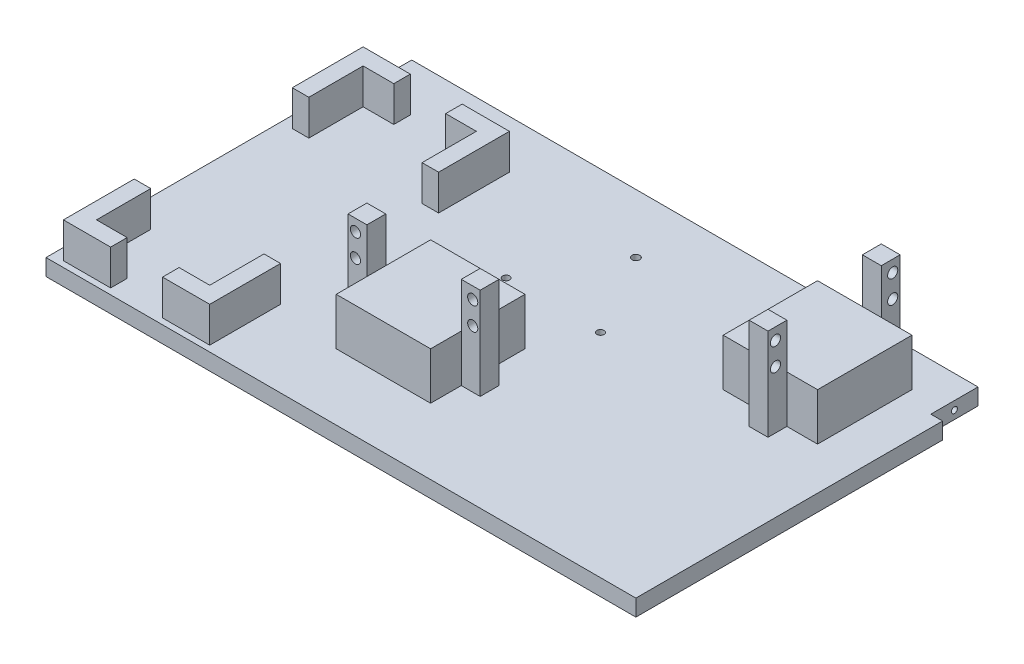
SolidWorks part; units mm, degrees
ref_plane "Ebene vorne" through (0, 0, 0) normal (0, 0, 1) x (1, 0, 0)
ref_plane "Ebene oben" through (0, 0, 0) normal (0, 1, 0) x (1, 0, 0)
ref_plane "Ebene rechts" through (0, 0, 0) normal (1, 0, 0) x (0, 0, -1)
sketch "Skizze1" plane through (0, 0, 0) normal (0, 1, 0) x (1, 0, 0)
  line L1 (-125, -125) -> (125, -125)
  line L2 (-125, -125) -> (-125, 125)
  line L3 (-125, 125) -> (125, 125)
  line L4 (125, -125) -> (125, 125)
  line L5 (-125, -125) -> (125, 125) construction
  line L6 (-125, 125) -> (125, -125) construction
  point P0 (0, 0)
  dimension "D1" = 250
  dimension "D2" = 250
extrude "Aufsatz-Linear austragen1" add sketch "Skizze1" along normal blind 5
sketch "Skizze2" plane through (0, 5, 0) normal (0, 1, 0) x (1, 0, 0)
  line L1 (-112.1275, -114.481) -> (-66.1275, -114.481)
  line L2 (-112.1275, -114.481) -> (-112.1275, -3.481)
  line L3 (-112.1275, -3.481) -> (-66.1275, -3.481)
  line L4 (-66.1275, -114.481) -> (-66.1275, -3.481)
  line L5 (-108.0153, 50.9925) -> (-23.0153, 50.9925)
  line L6 (-108.0153, 50.9925) -> (-108.0153, 110.9925)
  line L7 (-108.0153, 110.9925) -> (-23.0153, 110.9925)
  line L8 (-23.0153, 50.9925) -> (-23.0153, 110.9925)
  line L9 (-20, -105) -> (20, -105)
  line L10 (-20, -105) -> (-20, -65)
  line L11 (-20, -65) -> (20, -65)
  line L12 (20, -105) -> (20, -65)
  line L13 (65, -20) -> (105, -20)
  line L14 (65, -20) -> (65, 20)
  line L15 (65, 20) -> (105, 20)
  line L16 (105, -20) -> (105, 20)
  line L17 (6.7738, 50.9925) -> (91.7738, 50.9925)
  line L18 (6.7738, 50.9925) -> (6.7738, 110.9925)
  line L19 (6.7738, 110.9925) -> (91.7738, 110.9925)
  line L20 (91.7738, 50.9925) -> (91.7738, 110.9925)
  line L21 (-125, 125) -> (-125, -125) construction
  line L22 (-125, -125) -> (125, -125) construction
  line L23 (-100.1275, -122.481) -> (-100.1275, 4.519)
  line L24 (-120.1275, -122.481) -> (-58.1275, -122.481)
  line L25 (-120.1275, -122.481) -> (-120.1275, 4.519)
  line L26 (-120.1275, 4.519) -> (-58.1275, 4.519)
  line L27 (-58.1275, -122.481) -> (-58.1275, 4.519)
  line L28 (-78.1275, -122.481) -> (-78.1275, 4.519)
  line L29 (-120.1275, -92.481) -> (-57.4038, -92.481)
  line L30 (-120.1275, -25.481) -> (-58.1275, -25.481)
  circle A0 centre (0, 0) radius 1.65
  dimension "D1" = 3.3
  dimension "D2" = 46
  dimension "D3" = 111
  dimension "D4" = 40
  dimension "D5" = 40
  dimension "D6" = 60
  dimension "D7" = 85
  dimension "D8" = 40
  dimension "D9" = 40
  dimension "D10" = 65
  dimension "D11" = 125
  dimension "D12" = 125
  dimension "D13" = 65
  dimension "D14" = 105
  dimension "D15" = 105
  dimension "D16" = 8
  dimension "D17" = 8
  dimension "D18" = 8
  dimension "D19" = 8
  dimension "D20" = 30
  dimension "D21" = 30
  dimension "D22" = 20
  dimension "D23" = 20
extrude "Aufsatz-Linear austragen2" add sketch "Skizze2" along normal blind 15 contours L29 L25 L24 L23 L1 L2 | L29 L4 L1 L28 L24 L27 | L4 L30 L27 L26 L28 L3 | L25 L30 L2 L3 L23 L26 | L9 L12 L11 L10 | L13 L16 L15 L14
sketch "Skizze3" plane through (0, 20, 0) normal (0, 1, 0) x (1, 0, 0)
  line L0 (65, -20) -> (65, 20) construction
  line L1 (-20, -105) -> (20, -105)
  line L2 (-20, -105) -> (-20, -65)
  line L3 (-20, -65) -> (20, -65)
  line L4 (20, -105) -> (20, -65)
  line L5 (65, -20) -> (105, -20)
  line L6 (65, -20) -> (65, 20)
  line L7 (65, 20) -> (105, 20)
  line L8 (105, -20) -> (105, 20)
  line L9 (70, -15) -> (100, -15)
  line L10 (70, -15) -> (70, 15)
  line L11 (70, 15) -> (100, 15)
  line L12 (100, -15) -> (100, 15)
  line L13 (-15, -100) -> (15, -100)
  line L14 (-15, -100) -> (-15, -70)
  line L15 (-15, -70) -> (15, -70)
  line L16 (15, -100) -> (15, -70)
  circle A0 centre (0, 0) radius 1.65
  dimension "D9" = 3.3
  dimension "D1" = 5
  dimension "D2" = 5
  dimension "D3" = 5
  dimension "D4" = 5
  dimension "D5" = 5
  dimension "D6" = 5
  dimension "D7" = 5
  dimension "D8" = 5
extrude "Schnitt-Linear austragen1" cut sketch "Skizze3" against normal blind 15 contours L14 L13 L16 L15 | L10 L9 L12 L11 | A0
sketch "Skizze4" plane through (0, 5, 0) normal (0, 1, 0) x (1, 0, 0)
  line L1 (-15, -100) -> (15, -100)
  line L2 (-15, -100) -> (-15, -70)
  line L3 (-15, -70) -> (15, -70)
  line L4 (15, -100) -> (15, -70)
  line L5 (70, -15) -> (100, -15)
  line L6 (70, -15) -> (70, 15)
  line L7 (70, 15) -> (100, 15)
  line L8 (100, -15) -> (100, 15)
  circle A0 centre (0, 0) radius 1.65
  dimension "D1" = 3.3
extrude "Schnitt-Linear austragen2" cut sketch "Skizze4" against normal blind 15
sketch "Skizze6" plane through (0, 20, 0) normal (0, 1, 0) x (1, 0, 0)
  line L1 (-20, -105) -> (20, -105)
  line L2 (-20, -105) -> (-20, -65)
  line L3 (-20, -65) -> (20, -65)
  line L4 (20, -105) -> (20, -65)
  line L5 (65, -20) -> (105, -20)
  line L6 (65, -20) -> (65, 20)
  line L7 (65, 20) -> (105, 20)
  line L8 (105, -20) -> (105, 20)
extrude "Aufsatz-Linear austragen3" add sketch "Skizze6" against normal blind 5
sketch "Skizze7" plane through (0, 5, 0) normal (0, 1, 0) x (1, 0, 0)
  line L12 (-20, -105) -> (20, -105)
  line L13 (-20, -105) -> (-20, -65)
  line L14 (-20, -65) -> (20, -65)
  line L15 (20, -105) -> (20, -65)
  line L16 (65, -20) -> (105, -20)
  line L17 (65, -20) -> (65, 20)
  line L18 (65, 20) -> (105, 20)
  line L19 (105, -20) -> (105, 20)
extrude "Schnitt-Linear austragen3" cut sketch "Skizze7" along normal blind 43
sketch "Skizze8" plane through (0, 5, 0) normal (0, 1, 0) x (1, 0, 0)
  line L1 (-15, -100) -> (15, -100)
  line L2 (-15, -100) -> (-15, -70)
  line L3 (-15, -70) -> (15, -70)
  line L4 (15, -100) -> (15, -70)
  line L5 (70, -15) -> (100, -15)
  line L6 (70, -15) -> (70, 15)
  line L7 (70, 15) -> (100, 15)
  line L8 (100, -15) -> (100, 15)
extrude "Aufsatz-Linear austragen4" add sketch "Skizze8" against normal blind 5
sketch "Skizze9" plane through (0, 5, 0) normal (0, 1, 0) x (1, 0, 0)
  line L0 (0, -71) -> (0, -34.8212)
  line L1 (-6, -116) -> (39, -116)
  line L2 (-6, -116) -> (-6, -71)
  line L3 (-6, -71) -> (39, -71)
  line L4 (39, -116) -> (39, -71)
  line L5 (71, -39) -> (116, -39)
  line L6 (71, -39) -> (71, 6)
  line L7 (71, 6) -> (116, 6)
  line L8 (116, -39) -> (116, 6)
  line L9 (71, 0) -> (36.9303, 0)
  line L10 (125, 125) -> (-125, 125) construction
  line L11 (125, -125) -> (125, 125) construction
  dimension "D1" = 45
  dimension "D2" = 45
  dimension "D3" = 45
  dimension "D4" = 45
  dimension "D5" = 71
  dimension "D6" = 71
  dimension "D7" = 6
  dimension "D8" = 6
  dimension "D9" = 125
  dimension "D10" = 125
extrude "Aufsatz-Linear austragen5" add sketch "Skizze9" along normal blind 15 contours L1 L4 L3 L2 | L5 L8 L7 L6
sketch "Skizze10" plane through (0, 5, 0) normal (0, 1, 0) x (1, 0, 0)
  line L0 (-6, -116) -> (-6, -71) construction
  line L1 (-6, -93) -> (-14, -93)
  line L2 (-6, -93) -> (-6, -85)
  line L3 (-6, -85) -> (-14, -85)
  line L4 (-14, -93) -> (-14, -85)
  line L5 (39, -116) -> (39, -71) construction
  line L6 (39, -93) -> (47, -93)
  line L7 (39, -93) -> (39, -85)
  line L8 (39, -85) -> (47, -85)
  line L9 (47, -93) -> (47, -85)
  line L15 (71, 6) -> (116, 6) construction
  line L16 (93, 6) -> (85, 6)
  line L17 (93, 6) -> (93, 14)
  line L18 (93, 14) -> (85, 14)
  line L19 (85, 6) -> (85, 14)
  line L22 (71, -39) -> (71, 6) construction
  line L23 (85, -39) -> (93, -39)
  line L24 (85, -39) -> (85, -47)
  line L25 (85, -47) -> (93, -47)
  line L26 (93, -39) -> (93, -47)
  line L27 (-6, -71) -> (39, -71) construction
  line L28 (-6, -71) -> (39, -71) construction
  dimension "D1" = 8
  dimension "D2" = 8
  dimension "D3" = 14
  dimension "D4" = 8
  dimension "D5" = 8
  dimension "D7" = 8
  dimension "D8" = 14
  dimension "D9" = 8
  dimension "D10" = 14
  dimension "D11" = 14
  dimension "D12" = 8
  dimension "D13" = 8
extrude "Aufsatz-Linear austragen6" add sketch "Skizze10" along normal blind 34 contours L7 L6 L9 L8 | L2 L1 L4 L3 | L24 L23 L26 L25 | L17 L16 L19 L18
sketch "Skizze11" plane through (0, 0, 85) normal (0, 0, -1) x (-1, 0, 0)
  line L0 (-47, 39) -> (-47, 5) construction
  line L1 (14, 39) -> (6, 39)
  line L2 (14, 39) -> (14, 20)
  line L3 (14, 20) -> (6, 20)
  line L4 (6, 39) -> (6, 20)
  line L5 (-39, 39) -> (-47, 39)
  line L6 (-39, 39) -> (-39, 20)
  line L7 (-39, 20) -> (-47, 20)
  line L8 (-47, 39) -> (-47, 20)
  line L9 (10.85, 31.9) -> (10.85, 26.5)
  line L10 (-43.85, 31.9) -> (-43.85, 26.5)
  circle A0 centre (10.85, 34.05) radius 2.15
  circle A1 centre (10.85, 24.35) radius 2.15
  circle A2 centre (-43.85, 34.05) radius 2.15
  circle A3 centre (-43.85, 24.35) radius 2.15
  dimension "D1" = 4.3
  dimension "D2" = 4.3
  dimension "D3" = 4.3
  dimension "D4" = 4.3
  dimension "D5" = 5.4
  dimension "D6" = 3.15
  dimension "D7" = 5.4
  dimension "D8" = 3.15
  dimension "D9" = 4.35
  dimension "D10" = 4.35
extrude "Schnitt-Linear austragen4" cut sketch "Skizze11" against normal blind 34 contours A0 | A1 | A2 | A3
sketch "Skizze12" plane through (0, 5, 0) normal (0, 1, 0) x (1, 0, 0)
  line L0 (71, 0) -> (57, 0)
  line L1 (71, -39) -> (71, 6) construction
  line L2 (125, 125) -> (-125, 125) construction
  line L3 (125, -125) -> (125, 125) construction
  line L4 (0, 0) -> (0, -71)
  line L6 (-6, -71) -> (39, -71) construction
  line L10 (-22.6064, -118.7348) -> (120.4564, -118.7348)
  line L11 (-22.6064, -118.7348) -> (-22.6064, 65.7516)
  line L12 (-22.6064, 65.7516) -> (120.4564, 65.7516)
  line L13 (120.4564, -118.7348) -> (120.4564, 65.7516)
  dimension "D1" = 14
  dimension "D2" = 125
  dimension "D3" = 68
  dimension "D4" = 57
  dimension "D5" = 71
extrude "Schnitt-Linear austragen5" cut sketch "Skizze12" along normal blind 60
sketch "Skizze13" plane through (0, 5, 0) normal (0, 1, 0) x (1, 0, 0)
  line L0 (107, 0) -> (130, 0)
  line L1 (-30, -97) -> (10, -97)
  line L2 (-30, -97) -> (-30, -57)
  line L3 (-30, -57) -> (10, -57)
  line L4 (10, -97) -> (10, -57)
  line L5 (67, -30) -> (107, -30)
  line L6 (67, -30) -> (67, 10)
  line L7 (67, 10) -> (107, 10)
  line L8 (107, -30) -> (107, 10)
  line L9 (-125, -125) -> (125, -125) construction
  line L12 (0, -97) -> (0, -120)
  line L15 (125, -125) -> (125, 125) construction
  dimension "D2" = 120
  dimension "D3" = 125
  dimension "D4" = 130
  dimension "D5" = 23
  dimension "D6" = 10
  dimension "D7" = 125
  dimension "D8" = 40
  dimension "D9" = 40
  dimension "D10" = 23
  dimension "D11" = 40
  dimension "D12" = 40
  dimension "D13" = 10
extrude "Aufsatz-Linear austragen7" add sketch "Skizze13" along normal blind 15 contours L1 L4 L3 L2 | L5 L8 L7 L6
sketch "Skizze14" plane through (0, 5, 0) normal (0, 1, 0) x (1, 0, 0)
  line L0 (-30, -97) -> (-30, -57) construction
  line L1 (-30, -84) -> (-38, -84)
  line L2 (-30, -84) -> (-30, -76)
  line L3 (-30, -76) -> (-38, -76)
  line L4 (-38, -84) -> (-38, -76)
  line L5 (10, -97) -> (10, -57) construction
  line L6 (10, -84) -> (18, -84)
  line L7 (10, -84) -> (10, -76)
  line L8 (10, -76) -> (18, -76)
  line L9 (18, -84) -> (18, -76)
  line L10 (67, -30) -> (107, -30) construction
  line L11 (86, -30) -> (94, -30)
  line L12 (86, -30) -> (86, -38)
  line L13 (86, -38) -> (94, -38)
  line L14 (94, -30) -> (94, -38)
  line L15 (67, 10) -> (107, 10) construction
  line L16 (94, 10) -> (86, 10)
  line L17 (94, 10) -> (94, 18)
  line L18 (94, 18) -> (86, 18)
  line L19 (86, 10) -> (86, 18)
  line L24 (107, -30) -> (107, 10) construction
  line L25 (107, -30) -> (107, 10) construction
  line L26 (-30, -97) -> (10, -97) construction
  dimension "D1" = 8
  dimension "D2" = 8
  dimension "D3" = 8
  dimension "D4" = 8
  dimension "D5" = 8
  dimension "D6" = 8
  dimension "D7" = 8
  dimension "D8" = 8
  dimension "D9" = 13
  dimension "D10" = 13
  dimension "D11" = 13
  dimension "D12" = 13
extrude "Aufsatz-Linear austragen8" add sketch "Skizze14" along normal blind 34
sketch "Skizze15" plane through (0, 5, 0) normal (0, 1, 0) x (1, 0, 0)
  line L0 (125, 125) -> (-125, 125) construction
  line L1 (-18.5, 111) -> (18.5, 111)
  line L2 (-18.5, 111) -> (-18.5, 125)
  line L3 (-18.5, 125) -> (18.5, 125)
  line L4 (18.5, 111) -> (18.5, 125)
  line L5 (-125, 125) -> (-125, -125) construction
  dimension "D1" = 14
  dimension "D2" = 37
  dimension "D3" = 106.5
extrude "Schnitt-Linear austragen6" cut sketch "Skizze15" against normal blind 10 contours L2 L1 L4 L3
sketch "Skizze16" plane through (0, 5, 0) normal (0, 1, 0) x (1, 0, 0)
  line L1 (-101.7331, 41.9857) -> (-51.7331, 41.9857)
  line L2 (-101.7331, 41.9857) -> (-101.7331, 111.9857)
  line L3 (-101.7331, 111.9857) -> (-51.7331, 111.9857)
  line L4 (-51.7331, 41.9857) -> (-51.7331, 111.9857)
  line L5 (27.6532, 40.8623) -> (112.6532, 40.8623)
  line L6 (27.6532, 40.8623) -> (27.6532, 96.6623)
  line L7 (27.6532, 96.6623) -> (112.6532, 96.6623)
  line L8 (112.6532, 40.8623) -> (112.6532, 96.6623)
  dimension "D1" = 70
  dimension "D2" = 50
  dimension "D3" = 85
  dimension "D4" = 55.8
extrude "Aufsatz-Linear austragen9" add sketch "Skizze16" along normal blind 1 contours L2 L1 L4 L3
sketch "Skizze17" plane through (0, 5, 0) normal (0, 1, 0) x (1, 0, 0)
  line L1 (24.3018, 42.8865) -> (109.3018, 42.8865)
  line L2 (24.3018, 42.8865) -> (24.3018, 98.6865)
  line L3 (24.3018, 98.6865) -> (109.3018, 98.6865)
  line L4 (109.3018, 42.8865) -> (109.3018, 98.6865)
  circle A0 centre (105.9518, 46.2865) radius 1.35
  circle A1 centre (105.9518, 95.2865) radius 1.35
  circle A2 centre (47.9518, 46.2865) radius 1.35
  circle A3 centre (47.9518, 95.2865) radius 1.35
  dimension "D3" = 2.7
  dimension "D4" = 2.7
  dimension "D5" = 2.7
  dimension "D6" = 2.7
  dimension "D1" = 85
  dimension "D2" = 55.8
  dimension "D7" = 49
  dimension "D8" = 3.4
  dimension "D9" = 49
  dimension "D10" = 3.4
  dimension "D11" = 58
  dimension "D12" = 58
  dimension "D13" = 3.35
  dimension "D14" = 3.35
extrude "Schnitt-Linear austragen7" cut sketch "Skizze17" against normal blind 21 contours A2 | A3 | A1 | A0
sketch "Skizze18" plane through (0, 0, 76) normal (0, 0, -1) x (-1, 0, 0)
  line L0 (34.85, 36.9) -> (34.85, 31.5)
  line L5 (-14.85, 36.9) -> (-14.85, 31.5)
  line L11 (-10, 43.425) -> (-18, 43.425)
  line L12 (-10, 43.425) -> (-10, 25)
  line L13 (-10, 25) -> (-18, 25)
  line L14 (-18, 43.425) -> (-18, 25)
  line L15 (-18, 39) -> (-18, 5) construction
  line L16 (-18, 5) -> (-10, 5) construction
  line L17 (38, 44) -> (30, 44)
  line L18 (38, 44) -> (38, 25)
  line L19 (38, 25) -> (30, 25)
  line L20 (30, 44) -> (30, 25)
  line L21 (38, 39) -> (38, 5) construction
  line L22 (30, 5) -> (38, 5) construction
  circle A4 centre (-14.85, 39.05) radius 2.15
  circle A5 centre (-14.85, 29.35) radius 2.15
  circle A6 centre (34.85, 39.05) radius 2.15
  circle A7 centre (34.85, 29.35) radius 2.15
  dimension "D2" = 4.3
  dimension "D6" = 4.3
  dimension "D7" = 4.3
  dimension "D3" = 4.3
  dimension "D4" = 5.4
  dimension "D5" = 4.35
  dimension "D8" = 4.35
  dimension "D9" = 5.4
  dimension "D10" = 3.15
  dimension "D11" = 0
  dimension "D12" = 20
  dimension "D13" = 3.15
  dimension "D14" = 0
  dimension "D15" = 20
extrude "Schnitt-Linear austragen8" cut sketch "Skizze18" against normal blind 21 contours A6 | A7 | A4 | A5
sketch "Skizze19" plane through (86, 0, 0) normal (-1, 0, 0) x (0, 0, 1)
  line L0 (34.8363, 36.9) -> (34.8363, 31.5)
  line L5 (-14.85, 36.9) -> (-14.85, 31.5)
  line L11 (37.9863, 44) -> (30, 44)
  line L12 (37.9863, 44) -> (37.9863, 25)
  line L13 (37.9863, 25) -> (30, 25)
  line L14 (30, 44) -> (30, 25)
  line L15 (30, 5) -> (38, 5) construction
  line L16 (30, 39) -> (30, 20) construction
  line L18 (-10, 43.7954) -> (-18, 43.7954)
  line L19 (-10, 43.7954) -> (-10, 25)
  line L20 (-10, 25) -> (-18, 25)
  line L21 (-18, 43.7954) -> (-18, 25)
  line L22 (-18, 39) -> (-18, 5) construction
  line L23 (-125, 5) -> (125, 5) construction
  circle A4 centre (34.8363, 39.05) radius 2.15
  circle A5 centre (34.8363, 29.35) radius 2.15
  circle A6 centre (-14.85, 39.05) radius 2.15
  circle A7 centre (-14.85, 29.35) radius 2.15
  dimension "D2" = 4.3
  dimension "D6" = 4.3
  dimension "D7" = 4.3
  dimension "D3" = 4.3
  dimension "D4" = 5.4
  dimension "D5" = 4.35
  dimension "D8" = 5.4
  dimension "D9" = 4.35
  dimension "D10" = 3.15
  dimension "D11" = 3.15
  dimension "D12" = 20
  dimension "D13" = 0
  dimension "D14" = 0
  dimension "D15" = 20
extrude "Schnitt-Linear austragen9" cut sketch "Skizze19" against normal blind 21 contours A4 | A5 | A6 | A7
sketch "Skizze20" plane through (0, 5, 0) normal (0, 1, 0) x (1, 0, 0)
  line L0 (125, -125) -> (125, 125) construction
  line L1 (125, 25) -> (-125, 25)
  line L2 (125, 25) -> (125, -125)
  line L3 (125, -125) -> (-125, -125)
  line L4 (-125, 25) -> (-125, -125)
  line L6 (-125, 25) -> (125, 25)
  line L7 (-125, 25) -> (-125, 125)
  line L8 (-125, 125) -> (125, 125)
  line L9 (125, 25) -> (125, 125)
  dimension "D1" = 150
extrude "Schnitt-Linear austragen10" cut sketch "Skizze20" along normal blind 22 and the other way blind 63 contours L1 L9 L8 L7
sketch "Skizze21" plane through (0, 5, 0) normal (0, 1, 0) x (1, 0, 0)
  line L1 (-125, 25) -> (-120, 25)
  line L2 (-125, 25) -> (-125, 5)
  line L3 (-125, 5) -> (-120, 5)
  line L4 (-120, 25) -> (-120, 5)
  line L5 (125, 25) -> (120, 25)
  line L6 (125, 25) -> (125, 5)
  line L7 (125, 5) -> (120, 5)
  line L8 (120, 25) -> (120, 5)
  dimension "D1" = 20
  dimension "D2" = 20
  dimension "D3" = 5
  dimension "D4" = 5
extrude "Schnitt-Linear austragen11" cut sketch "Skizze21" against normal blind 10
sketch "Skizze22" plane through (-120, 0, 0) normal (-1, 0, 0) x (0, 0, 1)
  line L0 (-5, 5) -> (-25, 5)
  line L1 (-5, 5) -> (-5, 0)
  line L2 (-5, 0) -> (-25, 0)
  line L3 (-25, 5) -> (-25, 0)
  circle A0 centre (-15, 1.5) radius 1.25
  dimension "D1" = 2.5
  dimension "D2" = 1.5
  dimension "D3" = 10
extrude "Schnitt-Linear austragen12" cut sketch "Skizze22" against normal blind 20 contours A0
sketch "Skizze23" plane through (120, 0, 0) normal (1, 0, 0) x (0, 0, -1)
  line L0 (25, 5) -> (5, 5)
  line L1 (25, 5) -> (25, 0)
  line L2 (25, 0) -> (5, 0)
  line L3 (5, 5) -> (5, 0)
  circle A0 centre (15, 1.5) radius 1.25
  dimension "D1" = 2.5
  dimension "D2" = 1.5
  dimension "D3" = 10
extrude "Schnitt-Linear austragen13" cut sketch "Skizze23" against normal blind 20 contours A0
sketch "Skizze24" plane through (0, 5, 0) normal (0, 1, 0) x (1, 0, 0)
  line L1 (-30, -45) -> (30, -45)
  line L2 (-30, -45) -> (-30, 25)
  line L3 (-30, 25) -> (30, 25)
  line L4 (30, -45) -> (30, 25)
  line L7 (30, -45) -> (-30, -45)
  line L8 (30, -45) -> (30, -30)
  line L9 (30, -30) -> (-30, -30)
  line L10 (-30, -45) -> (-30, -30)
  circle A0 centre (-20, -35) radius 1.5
  circle A1 centre (20, -35) radius 1.5
  dimension "D5" = 3
  dimension "D6" = 3
  dimension "D1" = 25
  dimension "D2" = 45
  dimension "D3" = 60
  dimension "D4" = 30
  dimension "D7" = 10
  dimension "D8" = 10
  dimension "D9" = 10
  dimension "D10" = 10
  dimension "D11" = 15
  dimension "D12" = 10
extrude "Schnitt-Linear austragen15" cut sketch "Skizze24" against normal blind 10 contours A0 | A1
sketch "Skizze25" plane through (0, 0, 0) normal (0, -1, 0) x (1, 0, 0)
  line L1 (125, 125) -> (-125, 125)
  line L2 (125, 125) -> (125, -5)
  line L3 (125, -5) -> (-125, -5)
  line L4 (-125, 125) -> (-125, -5)
  line L5 (-120, -25) -> (120, -25)
  line L6 (-120, -25) -> (-120, -5)
  line L7 (-120, -5) -> (120, -5)
  line L8 (120, -25) -> (120, -5)
  circle A0 centre (20, 35) radius 1.5
  circle A1 centre (-20, 35) radius 1.5
  circle A2 centre (0, 0) radius 1.65
  circle M9 centre (-20, 35) radius 1.5
  circle M10 centre (20, 35) radius 1.5
  line M11 (-120, -5) -> (-120, -25)
  line M12 (-120, -25) -> (120, -25)
  line M13 (120, -25) -> (120, -5)
  line M14 (120, -5) -> (125, -5)
  line M15 (125, -5) -> (125, 125)
  line M16 (125, 125) -> (-125, 125)
  line M17 (-125, 125) -> (-125, -5)
  line M18 (-125, -5) -> (-120, -5)
  circle M19 centre (0, 0) radius 1.65
extrude "Aufsatz-Linear austragen10" add sketch "Skizze25" along normal blind 2 contours L3 M13 M11 M12 | L3 M14 M15 M16 M17 M18 M10 M19 M9
sketch "Skizze26" plane through (0, 20, 0) normal (0, 1, 0) x (1, 0, 0)
  line L0 (-112.1275, -25.481) -> (-112.1275, -3.481) construction
  line L1 (-65.1275, -115.481) -> (-113.1275, -115.481)
  line L2 (-65.1275, -115.481) -> (-65.1275, -2.481)
  line L3 (-65.1275, -2.481) -> (-113.1275, -2.481)
  line L4 (-113.1275, -115.481) -> (-113.1275, -2.481)
  line L5 (-66.1275, -25.481) -> (-66.1275, -3.481) construction
  line L6 (-78.1275, -3.481) -> (-66.1275, -3.481) construction
  line L8 (-78.1275, -114.481) -> (-66.1275, -114.481) construction
  dimension "D1" = 1
  dimension "D2" = 1
  dimension "D3" = 1
  dimension "D4" = 1
extrude "Schnitt-Linear austragen17" cut sketch "Skizze26" against normal blind 15 contours L2 L1 L4 L3
sketch "Skizze27" plane through (0, 20, 0) normal (0, 1, 0) x (1, 0, 0)
  line L1 (107, -30) -> (67, -30)
  line L2 (107, -30) -> (107, 10)
  line L3 (107, 10) -> (67, 10)
  line L4 (67, -30) -> (67, 10)
  line L5 (10, -57) -> (-30, -57)
  line L6 (10, -57) -> (10, -97)
  line L7 (10, -97) -> (-30, -97)
  line L8 (-30, -57) -> (-30, -97)
extrude "Aufsatz-Linear austragen11" add sketch "Skizze27" along normal blind 4
sketch "Skizze28" plane through (0, 39, 0) normal (0, 1, 0) x (1, 0, 0)
  line L1 (18, -84) -> (10, -84)
  line L2 (18, -84) -> (18, -76)
  line L3 (18, -76) -> (10, -76)
  line L4 (10, -84) -> (10, -76)
  line L5 (-30, -76) -> (-38, -76)
  line L6 (-30, -76) -> (-30, -84)
  line L7 (-30, -84) -> (-38, -84)
  line L8 (-38, -76) -> (-38, -84)
  line L9 (94, -38) -> (86, -38)
  line L10 (94, -38) -> (94, -30)
  line L11 (94, -30) -> (86, -30)
  line L12 (86, -38) -> (86, -30)
  line L13 (94, 10) -> (86, 10)
  line L14 (94, 10) -> (94, 18)
  line L15 (94, 18) -> (86, 18)
  line L16 (86, 10) -> (86, 18)
extrude "Aufsatz-Linear austragen12" add sketch "Skizze28" along normal blind 4
sketch "Skizze30" plane through (86, 0, 0) normal (-1, 0, 0) x (0, 0, 1)
  line L0 (32.6869, 39) -> (36.9857, 39) construction
  circle A0 centre (34.8363, 39) radius 2.15
  dimension "D1" = 4.3
extrude "Schnitt-Linear austragen18" cut sketch "Skizze30" against normal blind 9 contours A0
sketch "Skizze31" plane through (86, 0, 0) normal (-1, 0, 0) x (0, 0, 1)
  line L0 (-16.9994, 39) -> (-12.7006, 39) construction
  circle A0 centre (-14.85, 39) radius 2.15
  dimension "D1" = 4.3
extrude "Schnitt-Linear austragen19" cut sketch "Skizze31" against normal blind 9
sketch "Skizze32" plane through (0, 0, 76) normal (0, 0, -1) x (-1, 0, 0)
  line L0 (-16.9994, 39) -> (-12.7006, 39) construction
  line L1 (32.7006, 39) -> (36.9994, 39) construction
  circle A0 centre (-14.85, 39) radius 2.15
  circle A1 centre (34.85, 39) radius 2.15
  dimension "D1" = 4.3
  dimension "D2" = 4.3
extrude "Schnitt-Linear austragen20" cut sketch "Skizze32" against normal blind 9
sketch "Skizze33" plane through (0, 24, 0) normal (0, 1, 0) x (1, 0, 0)
  line L1 (-30, -97) -> (10, -97)
  line L2 (-30, -97) -> (-30, -57)
  line L3 (-30, -57) -> (10, -57)
  line L4 (10, -97) -> (10, -57)
  line L5 (67, -30) -> (107, -30)
  line L6 (67, -30) -> (67, 10)
  line L7 (67, 10) -> (107, 10)
  line L8 (107, -30) -> (107, 10)
extrude "Aufsatz-Linear austragen13" add sketch "Skizze33" along normal blind 1
sketch "Skizze34" plane through (0, 43, 0) normal (0, 1, 0) x (1, 0, 0)
  line L1 (-38, -84) -> (-30, -84)
  line L2 (-38, -84) -> (-38, -76)
  line L3 (-38, -76) -> (-30, -76)
  line L4 (-30, -84) -> (-30, -76)
  line L5 (10, -84) -> (18, -84)
  line L6 (10, -84) -> (10, -76)
  line L7 (10, -76) -> (18, -76)
  line L8 (18, -84) -> (18, -76)
  line L9 (94, -38) -> (86, -38)
  line L10 (94, -38) -> (94, -30)
  line L11 (94, -30) -> (86, -30)
  line L12 (86, -38) -> (86, -30)
  line L13 (86, 10) -> (94, 10)
  line L14 (86, 10) -> (86, 18)
  line L15 (86, 18) -> (94, 18)
  line L16 (94, 10) -> (94, 18)
extrude "Aufsatz-Linear austragen14" add sketch "Skizze34" along normal blind 1 contours L2 L1 L4 L3 | L6 L5 L8 L7 | L10 L9 L12 L11 | L14 L13 L16 L15
